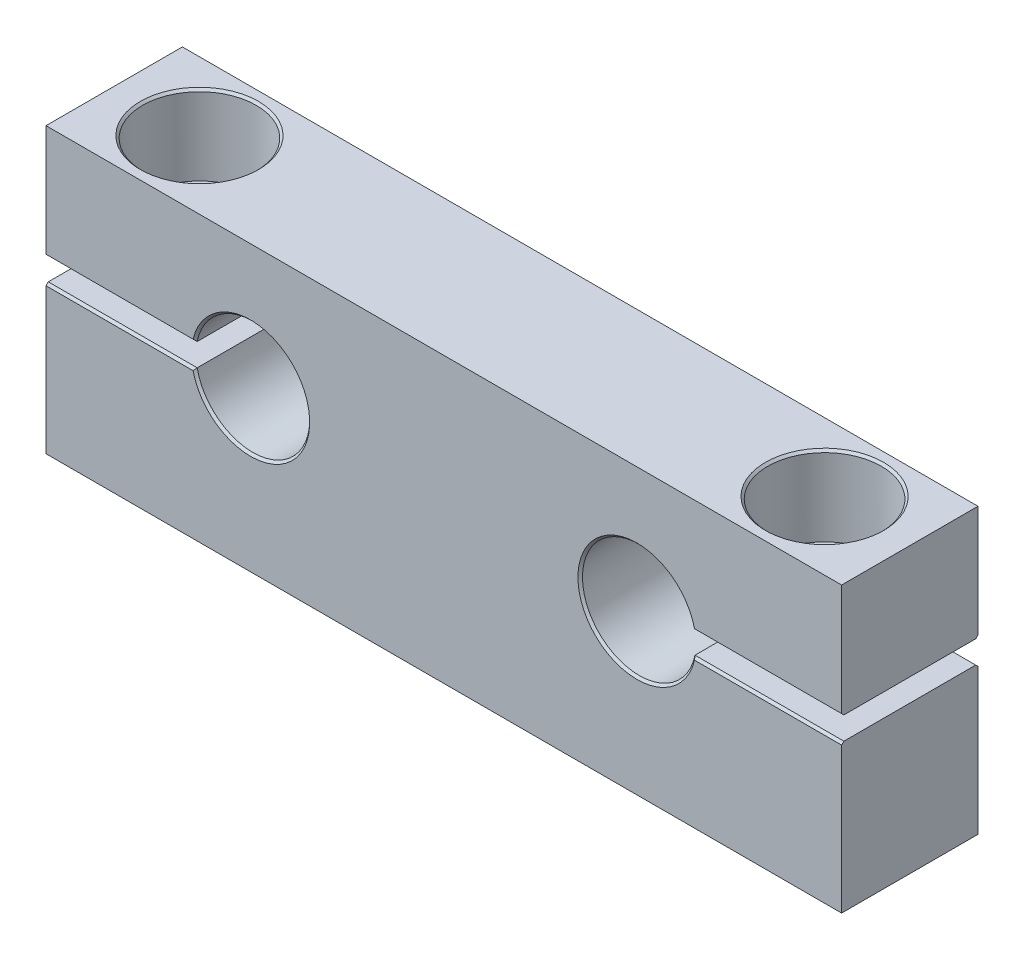
SolidWorks part; units mm, degrees
ref_plane "Front Plane" through (0, 0, 0) normal (0, 0, 1) x (1, 0, 0)
ref_plane "Top Plane" through (0, 0, 0) normal (0, 1, 0) x (1, 0, 0)
ref_plane "Right Plane" through (0, 0, 0) normal (1, 0, 0) x (0, 0, -1)
sketch "Sketch1" plane through (0, 0, 0) normal (0, 0, 1) x (1, 0, 0)
  line L0 (-35, 1.5) -> (35, 1.5) construction
  line L1 (-35, 12.5) -> (35, 12.5) construction
  line L2 (-35, 12.5) -> (-35, -12.5) construction
  line L3 (-35, -12.5) -> (35, -12.5) construction
  line L4 (35, 12.5) -> (35, -12.5) construction
  line L5 (0, -12.5) -> (0, 12.5) construction
  line L6 (-35, 0) -> (35, 0) construction
  circle A0 centre (-17, 1.5) radius 5 construction
  circle A1 centre (-27.5, 1.5) radius 2.75 construction
  point P0 (0, 0)
  dimension "Shaft Diameter (d)" = 10
  dimension "Mounting Hole Diameter (S)" = 5.5
  dimension "Overall Length (A)" = 70
  dimension "Overall Height (H)" = 25
  dimension "Center Height (H2)" = 14
  dimension "Center-to-Center Length (R)" = 34
  dimension "Mounting Hole Center-to-Center (E)" = 55
sketch "Sketch2" plane through (0, 0, 0) normal (1, 0, 0) x (0, 0, -1)
  line L1 (-6, -12.5) -> (6, -12.5) construction
  line L2 (-6, -12.5) -> (-6, 12.5) construction
  line L3 (-6, 12.5) -> (6, 12.5) construction
  line L4 (6, -12.5) -> (6, 12.5) construction
  line L5 (0, 12.5) -> (0, -12.5) construction
  line L6 (-6, 0) -> (6, 0) construction
  point P0 (0, 0)
  dimension "Overall Width (B)" = 12
sketch "Sketch3" plane through (0, 0, 0) normal (0, 0, 1) x (1, 0, 0)
  line L0 (-35, -12.5) -> (35, -12.5) construction
  line L1 (-35, 12.5) -> (0, 12.5)
  line L3 (-35, -12.5) -> (0, -12.5)
  line L4 (0, 12.5) -> (0, -12.5) construction
  line L5 (-35, 0.5) -> (-21.899, 0.5)
  line L6 (-35, 2.5) -> (-21.899, 2.5)
  line L7 (-35, 2.5) -> (-35, 0.5) construction
  line L10 (-35, 2.5) -> (-35, 12.5)
  line L11 (0, 12.5) -> (0, -12.5)
  line L13 (-35, -12.5) -> (-35, 0.5)
  circle A0 centre (-17, 1.5) radius 5 construction
  arc A1 (-21.899, 0.5) -> (-21.899, 2.5) centre (-17, 1.5) ccw
  point P13 (-35, 1.5)
  dimension "D1" = 2
extrude "Boss-Extrude1" add sketch "Sketch3" along normal up to vertex (6 mm away) and the other way up to vertex (6 mm away) up to point (0, 12.5, 6) other way up to point (0, 12.5, -6)
sketch "Sketch5" plane through (0, 0, 0) normal (0, 0, 1) x (1, 0, 0)
  line L0 (-32.5, 12.5) -> (-32.5, 5.5)
  line L1 (-35, 12.5) -> (35, 12.5) construction
  line L2 (-32.5, 5.5) -> (-22.5, 5.5) construction
  line L3 (-22.5, 5.5) -> (-22.5, 12.5) construction
  line L4 (-30.25, 5.5) -> (-30.25, -12.5)
  line L5 (-35, -12.5) -> (35, -12.5) construction
  line L6 (-32.5, 12.5) -> (-27.5, 12.5)
  line L7 (-27.5, 5.5) -> (-27.5, 1.5)
  line L8 (-30.25, 5.5) -> (-32.5, 5.5)
  line L9 (-27.5, 12.5) -> (-27.5, 5.5)
  line L10 (-27.5, 1.5) -> (-27.5, -12.5)
  line L11 (-27.5, -12.5) -> (-30.25, -12.5)
  line L12 (-24.75, 1.5) -> (-24.75, 5.5) construction
  line L13 (-35, 1.5) -> (35, 1.5) construction
  line L14 (-24.75, 1.5) -> (-24.75, -12.5) construction
  line L15 (-24.75, 5.5) -> (-22.5, 5.5) construction
  line L16 (0, 0) -> (0, 12.5) construction
  line L17 (-35, 0) -> (35, 0) construction
  line L18 (32.5, 12.5) -> (32.5, 5.5) construction
  line L19 (24.75, 1.5) -> (24.75, -12.5) construction
  line L20 (24.75, 1.5) -> (24.75, 5.5) construction
  line L21 (30.25, 5.5) -> (30.25, -12.5) construction
  line L22 (27.5, 1.5) -> (27.5, -12.5) construction
  line L23 (27.5, 5.5) -> (27.5, 1.5) construction
  line L24 (27.5, 12.5) -> (27.5, 5.5) construction
  line L25 (32.5, 5.5) -> (22.5, 5.5) construction
  line L26 (22.5, 5.5) -> (22.5, 12.5) construction
  line L27 (32.5, 12.5) -> (27.5, 12.5) construction
  line L28 (27.5, 12.5) -> (22.5, 12.5) construction
  circle A1 centre (-27.5, 1.5) radius 2.75 construction
  dimension "Counter Bore Dia" = 10
  dimension "Counter Bore Dp" = 7
revolve "Cut-Revolve1" cut sketch "Sketch5" angle 360 about L9
chamfer "Chamfer1" distance 0.2 angle 45 8 edges at (-28.4495, 0.5, -6) (-12, 1.5, -6) (-28.4495, 2.5, -6) (-28.4495, 2.5, 6) (-28.4495, 0.5, 6) (-12, 1.5, 6) (-32.5, 12.5, 0) (-30.25, -12.5, 0)
mirror "Mirror1" about plane through (0, 0, 0) normal (1, 0, 0) of bodies 105
